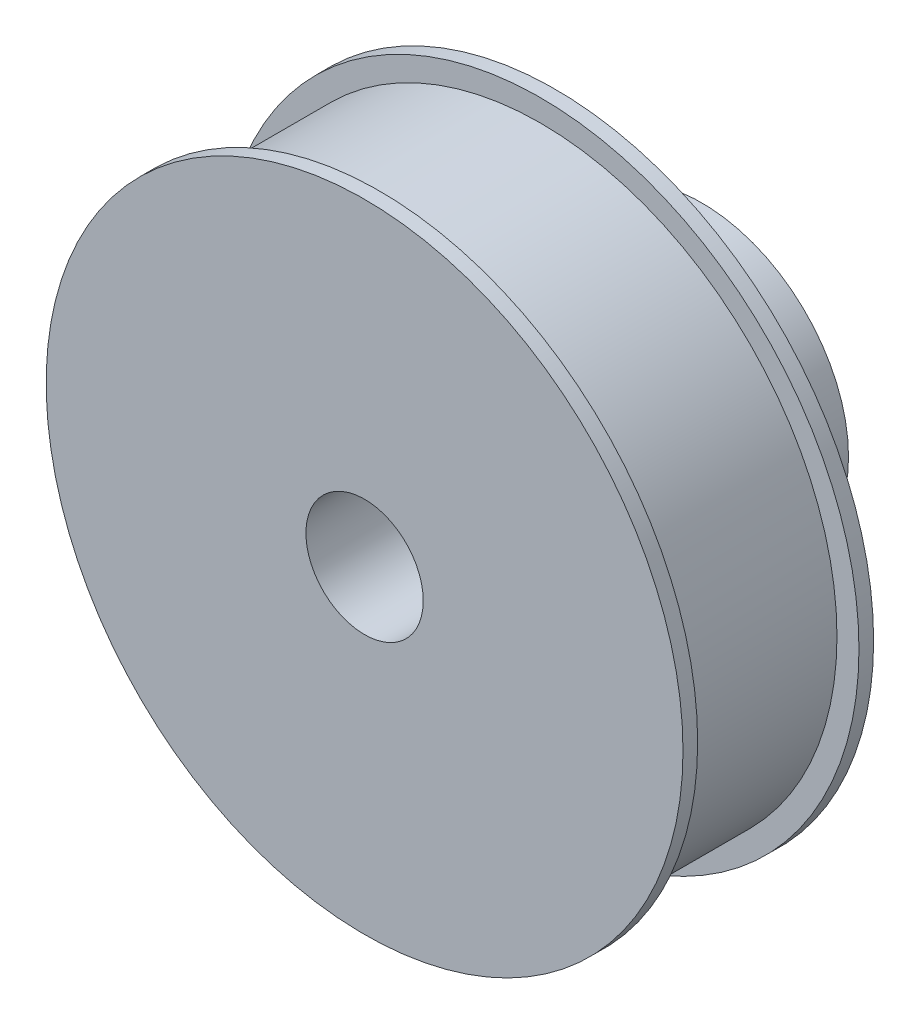
SolidWorks part; units mm, degrees
ref_plane "Front Plane" through (0, 0, 0) normal (0, 0, 1) x (1, 0, 0)
ref_plane "Top Plane" through (0, 0, 0) normal (0, 1, 0) x (1, 0, 0)
ref_plane "Right Plane" through (0, 0, 0) normal (1, 0, 0) x (0, 0, -1)
sketch "Sketch1" plane through (0, 0, 0) normal (0, 1, 0) x (1, 0, 0)
  line L0 (0, 0) -> (0, 161.9291) construction
  line L1 (0, 23) -> (-10, 23)
  line L2 (-10, 23) -> (-10, 13)
  line L3 (-10, 13) -> (-21.7127, 13)
  line L4 (-21.7127, 13) -> (-21.7127, 12)
  line L5 (-21.7127, 12) -> (-20.2127, 12)
  line L6 (-20.2127, 12) -> (-20.2127, 1)
  line L7 (-20.2127, 1) -> (-21.7127, 1)
  line L8 (-21.7127, 1) -> (-21.7127, 0)
  line L9 (-21.7127, 0) -> (0, 0)
  line L10 (0, 0) -> (0, 23)
  line L11 (-21.7127, 12) -> (-21.7127, 1) construction
  dimension "D1" = 20.2127
  dimension "D2" = 1.5
  dimension "D3" = 11
  dimension "D4" = 1
  dimension "D5" = 1
  dimension "D6" = 10
  dimension "D7" = 10
revolve "Revolve1" add sketch "Sketch1" angle 360 about L10
sketch "Sketch2" plane through (0, 0, 0) normal (0, 0, 1) x (1, 0, 0)
  circle A0 centre (0, 0) radius 4
  circle A1 centre (0, 0) radius 21.7127 construction
  dimension "D1" = 8
extrude "Cut-Extrude1" cut sketch "Sketch2" against normal through all
sketch "Sketch3" plane through (0, 0, 0) normal (0, 1, 0) x (1, 0, 0)
  line L0 (0, 23) -> (0, 13) construction
  line L1 (10, 23) -> (-10, 23) construction
  circle A0 centre (0, 18) radius 1.5
  dimension "D1" = 5
  dimension "D2" = 3
extrude "Cut-Extrude2" cut sketch "Sketch3" against normal through all
sketch "Sketch4" plane through (0, 0, 0) normal (1, 0, 0) x (0, 0, -1)
  line L0 (23, 0) -> (13, 0) construction
  line L1 (23, -10) -> (23, 10) construction
  circle A0 centre (18, 0) radius 1.5
  dimension "D1" = 5
  dimension "D2" = 3
extrude "Cut-Extrude3" cut sketch "Sketch4" against normal through all
ref_plane "Plane1" through (0, 0, -6.5) normal (0, 0, 1) x (1, 0, 0)
equation "\"teeth\"= 25"
equation "\"pitch\"= .2in"
equation "\"pitch diameter\"= \"teeth\" * \"pitch\" / pi"
equation "\"D1@Sketch1\"=\"pitch diameter\"/2"
